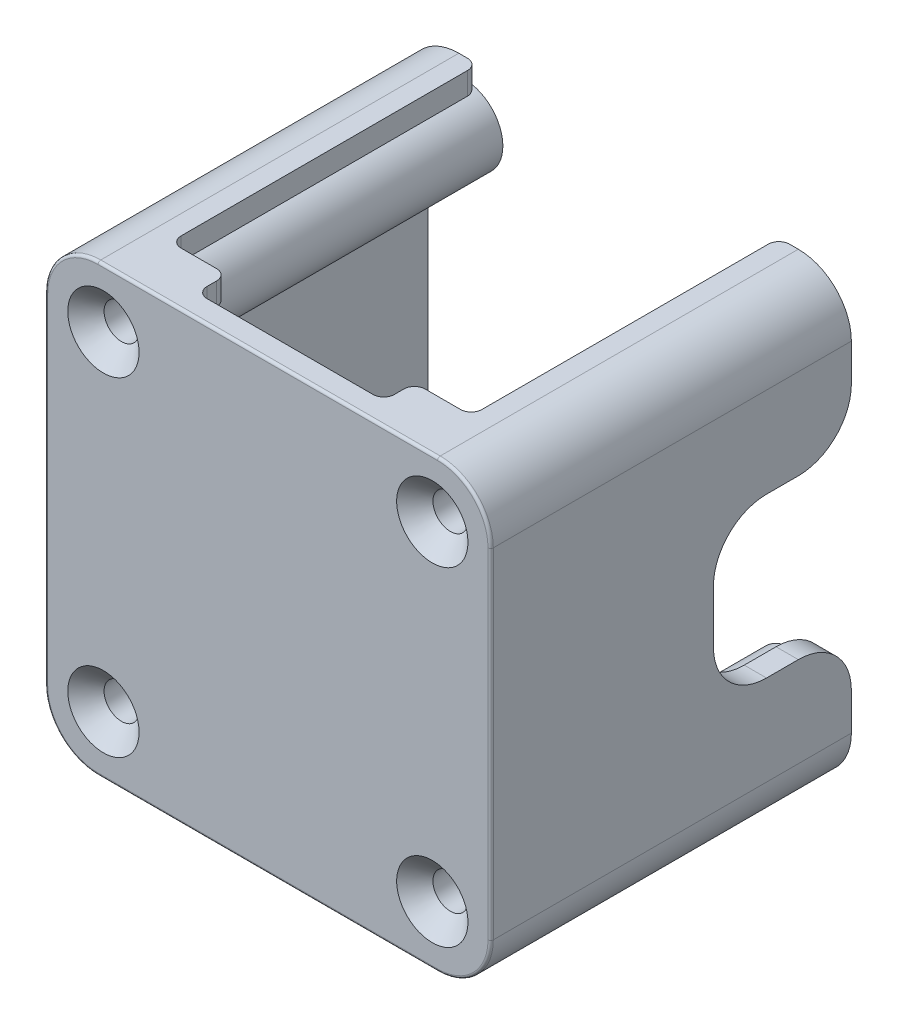
SolidWorks part; units mm, degrees
ref_plane "Alzado" through (0, 0, 0) normal (0, 0, 1) x (1, 0, 0)
ref_plane "Planta" through (0, 0, 0) normal (0, 1, 0) x (1, 0, 0)
ref_plane "Vista lateral" through (0, 0, 0) normal (1, 0, 0) x (0, 0, -1)
sketch "Croquis1" plane through (0, 0, 0) normal (0, 0, 1) x (1, 0, 0)
  line L1 (-18.3779, 26.2769) -> (23.6221, 26.2769)
  line L2 (-18.3779, 26.2769) -> (-18.3779, -15.7231)
  line L3 (-18.3779, -15.7231) -> (23.6221, -15.7231)
  line L4 (23.6221, 26.2769) -> (23.6221, -15.7231)
  dimension "D1" = 42
extrude "Saliente-Extruir1" add sketch "Croquis1" against normal blind 34
fillet "Redondeo1" radius 5 4 edges at (23.6221, -15.7231, -17) (-18.3779, -15.7231, -17) (-18.3779, 26.2769, -17) (23.6221, 26.2769, -17)
shell "Vaciado1" thickness 2.1
sketch "Croquis2" plane through (0, 26.2769, 0) normal (0, 1, 0) x (1, 0, 0)
  line L0 (-11.5579, 34) -> (16.7921, 34)
  line L1 (18.6221, 34) -> (-13.3779, 34) construction
  line L2 (16.7921, 34) -> (16.7921, 5)
  line L3 (16.7921, 5) -> (11.4421, 5)
  line L4 (11.4421, 5) -> (11.4421, 2.1)
  line L5 (11.4421, 2.1) -> (-6.2079, 2.1)
  line L6 (-6.2079, 2.1) -> (-6.2079, 5)
  line L7 (-6.2079, 5) -> (-11.5579, 5)
  line L8 (-11.5579, 5) -> (-11.5579, 34)
  line L9 (23.6221, 34) -> (23.6221, 0) construction
  dimension "D1" = 29
  dimension "D2" = 2.9
  dimension "D3" = 5.35
  dimension "D4" = 17.65
  dimension "D5" = 6.83
extrude "Cortar-Extruir1" cut sketch "Croquis2" against normal through all
sketch "Croquis4" plane through (23.6221, 0, 0) normal (1, 0, 0) x (0, 0, -1)
  line L0 (34, 12.7769) -> (21, 12.7769)
  line L1 (34, -10.7231) -> (34, 21.2769) construction
  line L2 (21, 12.7769) -> (21, -2.2231)
  line L3 (21, -2.2231) -> (34, -2.2231)
  line L4 (34, -2.2231) -> (34, 12.7769)
  line L5 (0, 26.2769) -> (34, 26.2769) construction
  dimension "D1" = 15
  dimension "D2" = 13
  dimension "D3" = 13.5
extrude "Cortar-Extruir2" cut sketch "Croquis4" against normal up to next
fillet "Redondeo2" radius 5 4 edges at (22.5721, 12.7769, -34) (22.5721, -2.2231, -34) (22.5721, -2.2231, -21) (22.5721, 12.7769, -21)
fillet "Redondeo3" radius 1 16 edges at (-11.5579, -14.6731, -5) (-6.2079, -14.6731, -5) (-6.2079, -14.6731, -2.1) (11.4421, -14.6731, -2.1) (11.4421, -14.6731, -5) (16.7921, -14.6731, -5) (-11.5579, 25.2269, -5) (-6.2079, 25.2269, -5) (-6.2079, 25.2269, -2.1) (11.4421, 25.2269, -2.1) (11.4421, 25.2269, -5) (16.7921, 25.2269, -5) (16.7921, -14.6731, -34) (-11.5579, -14.6731, -34) (16.7921, 25.2269, -34) (-11.5579, 25.2269, -34)
fillet "Redondeo4" radius 0.25 8 edges at (-16.9134, -14.2586, 0) (-18.3779, 5.2769, 0) (-16.9134, 24.8125, 0) (2.6221, 26.2769, 0) (22.1577, 24.8125, 0) (23.6221, 5.2769, 0) (22.1577, -14.2586, 0) (2.6221, -15.7231, 0)
sketch "Croquis5" plane through (0, 0, -2.1) normal (0, 0, -1) x (-1, 0, 0)
  line L0 (-18.6221, 26.2769) -> (-17.7921, 26.2769) construction
  line L1 (-23.6221, 17.7769) -> (-23.6221, 21.2769) construction
  circle A0 centre (-18.1221, 20.7769) radius 3.65
  circle A1 centre (12.8779, 20.7769) radius 3.65
  circle A2 centre (-18.1221, -10.2231) radius 3.65
  circle A3 centre (12.8779, -10.2231) radius 3.65
  point P0 (-18.1221, 20.7769)
  point P1 (12.8779, -10.2231)
  point P2 (12.8779, 20.7769)
  point P5 (-18.1221, -10.2231)
  dimension "D7" = 7.3
  dimension "D1" = 5.5
  dimension "D2" = 5.5
  dimension "D3" = 2
  dimension "D4" = 31
  dimension "D5" = 31
  dimension "D6" = 31
extrude "Saliente-Extruir2" add sketch "Croquis5" along direction (0, 0, 1) on the side of the normal up to surface (31.9 mm away)
sketch "Croquis8" plane through (0, 0, 0) normal (0, 0, 1) x (1, 0, 0)
  line L1 (-13.3779, 26.2769) -> (18.6221, 26.2769) construction
  point P0 (-12.8779, 20.7769)
  point P1 (18.1221, 20.7769)
  point P2 (18.1221, -10.2231)
  point P3 (-12.8779, -10.2231)
  dimension "D1" = 31
  dimension "D2" = 31
  dimension "D3" = 31
  dimension "D4" = 5.5
  dimension "D5" = 5.5
hole_wizard "Refrentado para tornillo tapón con cabeza plana de clavija de M31" positions "Croquis13" profile "Croquis15" countersink size "M3" standard "Ansi Metric" end condition through all
sketch "Croquis13" plane through (0, 0, 0) normal (0, 0, 1) x (1, 0, 0)
  point P0 (-12.8779, 20.7769)
  point P3 (-12.8779, -10.2231)
  point P6 (18.1221, -10.2231)
  point P9 (18.1221, 20.7769)
sketch "Croquis15" plane through (-12.8779, 20.7769, 0) normal (1, 0, 0) x (0, -1, 0)
  line L0 (0, 0) -> (0, 34)
  line L1 (0, 34) -> (1.65, 34)
  line L2 (1.65, 34) -> (1.65, 1.71)
  line L3 (1.65, 1.71) -> (3.36, 0)
  line L5 (3.36, 0) -> (0, 0)
  line L6 (-1.65, 1.71) -> (-3.36, 0) construction
  line L11 (0, -6.35) -> (0, 107.95) construction
  dimension "Diámetro de taladro hasta el siguiente" = 3.3
  dimension "Profundidad de taladro hasta el siguiente" = 34
  dimension "Diámetro de avellanado cercano" = 6.72
  dimension "Ángulo de avellanado cercano" = 90
sketch "Croquis16" plane through (0, 0, -2.1) normal (0, 0, -1) x (-1, 0, 0)
  line L0 (-23.6221, 26.2769) -> (18.3779, 26.2769) construction
  line L2 (18.3779, 21.2769) -> (18.3779, -10.7231) construction
  line L3 (-23.6221, 17.7769) -> (-23.6221, 21.2769) construction
  line L4 (-2.6221, 26.2769) -> (-2.6171, -15.7231) construction
  line L5 (5.2079, -15.7231) -> (-10.4421, -15.7231) construction
  line L6 (-8.3017, 11.7107) -> (-8.3017, 14.8175)
  line L7 (-8.3017, 14.8175) -> (-8.3017, 8.6038)
  line L8 (3.0601, 14.8188) -> (3.0616, 8.6052)
  circle A0 centre (-10.1204, 11.7107) radius 1.3
  arc A1 (-8.3017, 14.8175) -> (-8.3017, 8.6038) centre (-10.1204, 11.7107) ccw
  circle A2 centre (4.8796, 11.7124) radius 1.3
  arc A3 (3.0601, 14.8188) -> (3.0616, 8.6052) centre (4.8796, 11.7124) cw
  dimension "D1" = 2.6
  dimension "D2" = 7.2
  dimension "D3" = 7.5
extrude "Saliente-Extruir3" add sketch "Croquis16" along normal blind 10 contours L6 A1 L7 A0 | A0 | A3 L8 A2
